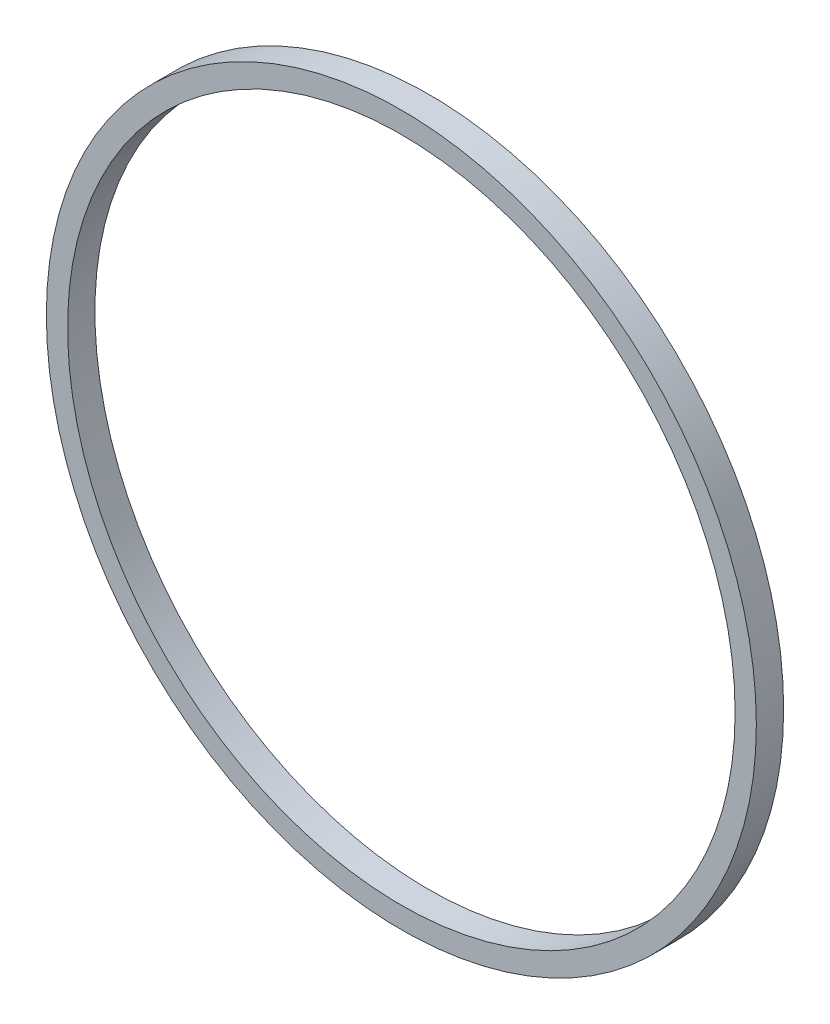
SolidWorks part; units mm, degrees
ref_plane "Front Plane" through (0, 0, 0) normal (0, 0, 1) x (1, 0, 0)
ref_plane "Top Plane" through (0, 0, 0) normal (0, 1, 0) x (1, 0, 0)
ref_plane "Right Plane" through (0, 0, 0) normal (1, 0, 0) x (0, 0, -1)
sketch "Sketch1" plane through (0, 0, 0) normal (0, 0, 1) x (1, 0, 0)
  arc B0 (18.6136, 163.5731) -> (18.6136, 4.963) centre (178.25, 84.268) ccw
  arc B1 (27.2098, 0) -> (164.5701, 79.305) centre (16.0718, 177.9017) ccw
  arc B2 (164.5701, 89.231) -> (27.2098, 168.5361) centre (16.0718, -9.3656) ccw
  circle B3 centre (70.1312, 84.268) radius 63.5
  circle B4 centre (70.1312, 84.268) radius 60
  circle B5 centre (70.1312, 84.268) radius 58.5
  circle B6 centre (70.1312, 84.268) radius 55
sketch_block_instance "sealsblock-1"
sketch_block "sealsblock"
extrude "Boss-Extrude1" add sketch "Sketch1" along normal blind 4.5 contours B5 B6
